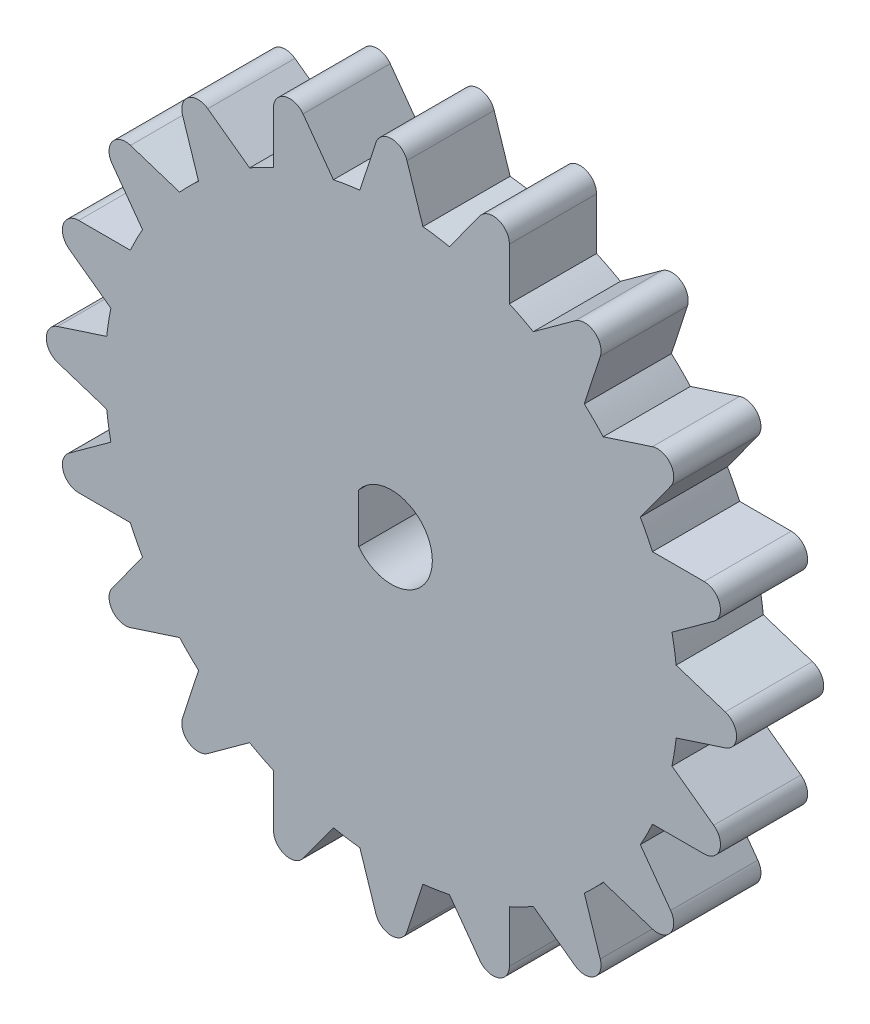
SolidWorks part; units mm, degrees
ref_plane "Płaszczyzna przednia" through (0, 0, 0) normal (0, 0, 1) x (1, 0, 0)
ref_plane "Płaszczyzna górna" through (0, 0, 0) normal (0, 1, 0) x (1, 0, 0)
ref_plane "Płaszczyzna prawa" through (0, 0, 0) normal (1, 0, 0) x (0, 0, -1)
sketch "Szkic1" plane through (0, 0, 0) normal (0, 0, 1) x (1, 0, 0)
  line L0 (-2, 1.5) -> (-2, -1.5)
  line L1 (-0.951, 20.3937) -> (-1.9259, 17.3937)
  line L2 (0, 27.2612) -> (0, -6.5612) construction
  line L3 (0.951, 20.3937) -> (1.9259, 17.3937)
  line L4 (7.2065, 19.1017) -> (7.2066, 15.9472)
  line L5 (5.3975, 19.6895) -> (3.5433, 17.1375)
  line L6 (12.7565, 15.9398) -> (11.7819, 12.9398)
  line L7 (11.2177, 17.0579) -> (8.6657, 15.2038)
  line L8 (17.0579, 11.2177) -> (15.2038, 8.6657)
  line L9 (15.9398, 12.7565) -> (12.9398, 11.7819)
  line L10 (19.6895, 5.3975) -> (17.1375, 3.5433)
  line L11 (19.1017, 7.2065) -> (15.9472, 7.2066)
  line L12 (20.3937, -0.951) -> (17.3937, -1.9259)
  line L13 (20.3937, 0.951) -> (17.3937, 1.9259)
  line L14 (19.1017, -7.2065) -> (15.9472, -7.2066)
  line L15 (19.6895, -5.3975) -> (17.1375, -3.5433)
  line L16 (15.9398, -12.7565) -> (12.9398, -11.7819)
  line L17 (17.0579, -11.2177) -> (15.2038, -8.6657)
  line L18 (11.2177, -17.0579) -> (8.6657, -15.2038)
  line L19 (12.7565, -15.9398) -> (11.7819, -12.9398)
  line L20 (5.3975, -19.6895) -> (3.5433, -17.1375)
  line L21 (7.2065, -19.1017) -> (7.2066, -15.9472)
  line L22 (-0.951, -20.3937) -> (-1.9259, -17.3937)
  line L23 (0.951, -20.3937) -> (1.9259, -17.3937)
  line L24 (-7.2065, -19.1017) -> (-7.2066, -15.9472)
  line L25 (-5.3975, -19.6895) -> (-3.5433, -17.1375)
  line L26 (-12.7565, -15.9398) -> (-11.7819, -12.9398)
  line L27 (-11.2177, -17.0579) -> (-8.6657, -15.2038)
  line L28 (-17.0579, -11.2177) -> (-15.2038, -8.6657)
  line L29 (-15.9398, -12.7565) -> (-12.9398, -11.7819)
  line L30 (-19.6895, -5.3975) -> (-17.1375, -3.5433)
  line L31 (-19.1017, -7.2065) -> (-15.9472, -7.2066)
  line L32 (-20.3937, 0.951) -> (-17.3937, 1.9259)
  line L33 (-20.3937, -0.951) -> (-17.3937, -1.9259)
  line L34 (-19.1017, 7.2065) -> (-15.9472, 7.2066)
  line L35 (-19.6895, 5.3975) -> (-17.1375, 3.5433)
  line L36 (-15.9398, 12.7565) -> (-12.9398, 11.7819)
  line L37 (-17.0579, 11.2177) -> (-15.2038, 8.6657)
  line L38 (-11.2177, 17.0579) -> (-8.6657, 15.2038)
  line L39 (-12.7565, 15.9398) -> (-11.7819, 12.9398)
  line L40 (-5.3975, 19.6895) -> (-3.5433, 17.1375)
  line L41 (-7.2065, 19.1017) -> (-7.2066, 15.9472)
  arc A0 (-2, -1.5) -> (-2, 1.5) centre (0, 0) ccw
  arc A1 (-1.9259, 17.3937) -> (-3.5433, 17.1375) centre (0, 0) ccw
  arc A2 (0.951, 20.3937) -> (-0.951, 20.3937) centre (0, 20.0846) ccw
  arc A3 (7.2065, 19.1017) -> (5.3975, 19.6895) centre (6.2065, 19.1016) ccw
  arc A4 (12.7565, 15.9398) -> (11.2177, 17.0579) centre (11.8055, 16.2488) ccw
  arc A5 (17.0579, 11.2177) -> (15.9398, 12.7565) centre (16.2488, 11.8055) ccw
  arc A6 (19.6895, 5.3975) -> (19.1017, 7.2065) centre (19.1016, 6.2065) ccw
  arc A7 (20.3937, -0.951) -> (20.3937, 0.951) centre (20.0846, 0) ccw
  arc A8 (19.1017, -7.2065) -> (19.6895, -5.3975) centre (19.1016, -6.2065) ccw
  arc A9 (15.9398, -12.7565) -> (17.0579, -11.2177) centre (16.2488, -11.8055) ccw
  arc A10 (11.2177, -17.0579) -> (12.7565, -15.9398) centre (11.8055, -16.2488) ccw
  arc A11 (5.3975, -19.6895) -> (7.2065, -19.1017) centre (6.2065, -19.1016) ccw
  arc A12 (-0.951, -20.3937) -> (0.951, -20.3937) centre (0, -20.0846) ccw
  arc A13 (-7.2065, -19.1017) -> (-5.3975, -19.6895) centre (-6.2065, -19.1016) ccw
  arc A14 (-12.7565, -15.9398) -> (-11.2177, -17.0579) centre (-11.8055, -16.2488) ccw
  arc A15 (-17.0579, -11.2177) -> (-15.9398, -12.7565) centre (-16.2488, -11.8055) ccw
  arc A16 (-19.6895, -5.3975) -> (-19.1017, -7.2065) centre (-19.1016, -6.2065) ccw
  arc A17 (-20.3937, 0.951) -> (-20.3937, -0.951) centre (-20.0846, 0) ccw
  arc A18 (-19.1017, 7.2065) -> (-19.6895, 5.3975) centre (-19.1016, 6.2065) ccw
  arc A19 (-15.9398, 12.7565) -> (-17.0579, 11.2177) centre (-16.2488, 11.8055) ccw
  arc A20 (-11.2177, 17.0579) -> (-12.7565, 15.9398) centre (-11.8055, 16.2488) ccw
  arc A21 (-5.3975, 19.6895) -> (-7.2065, 19.1017) centre (-6.2065, 19.1016) ccw
  arc A22 (3.5433, 17.1375) -> (1.9259, 17.3937) centre (0, 0) ccw
  arc A23 (8.6657, 15.2038) -> (7.2066, 15.9472) centre (0, 0) ccw
  arc A24 (12.9398, 11.7819) -> (11.7819, 12.9398) centre (0, 0) ccw
  arc A25 (15.9472, 7.2066) -> (15.2038, 8.6657) centre (0, 0) ccw
  arc A26 (17.3937, 1.9259) -> (17.1375, 3.5433) centre (0, 0) ccw
  arc A27 (17.1375, -3.5433) -> (17.3937, -1.9259) centre (0, 0) ccw
  arc A28 (15.2038, -8.6657) -> (15.9472, -7.2066) centre (0, 0) ccw
  arc A29 (11.7819, -12.9398) -> (12.9398, -11.7819) centre (0, 0) ccw
  arc A30 (7.2066, -15.9472) -> (8.6657, -15.2038) centre (0, 0) ccw
  arc A31 (1.9259, -17.3937) -> (3.5433, -17.1375) centre (0, 0) ccw
  arc A32 (-3.5433, -17.1375) -> (-1.9259, -17.3937) centre (0, 0) ccw
  arc A33 (-8.6657, -15.2038) -> (-7.2066, -15.9472) centre (0, 0) ccw
  arc A34 (-12.9398, -11.7819) -> (-11.7819, -12.9398) centre (0, 0) ccw
  arc A35 (-17.3937, -1.9259) -> (-17.1375, -3.5433) centre (0, 0) ccw
  arc A36 (-17.1375, 3.5433) -> (-17.3937, 1.9259) centre (0, 0) ccw
  arc A37 (-15.9472, -7.2066) -> (-15.2038, -8.6657) centre (0, 0) ccw
  arc A38 (-15.2038, 8.6657) -> (-15.9472, 7.2066) centre (0, 0) ccw
  arc A39 (-11.7819, 12.9398) -> (-12.9398, 11.7819) centre (0, 0) ccw
  arc A40 (-7.2066, 15.9472) -> (-8.6657, 15.2038) centre (0, 0) ccw
  point P12 (0, 23.3204)
  point P110 (0, 0)
  dimension "D1" = 5
  dimension "D3" = 1
  dimension "D4" = 35
  dimension "D2" = 2
  dimension "D5" = 18.002
  dimension "D6" = 3
  dimension "D7" = 20
extrude "Dodanie-wyciągnięcie1" add sketch "Szkic1" along normal blind 5.3251
